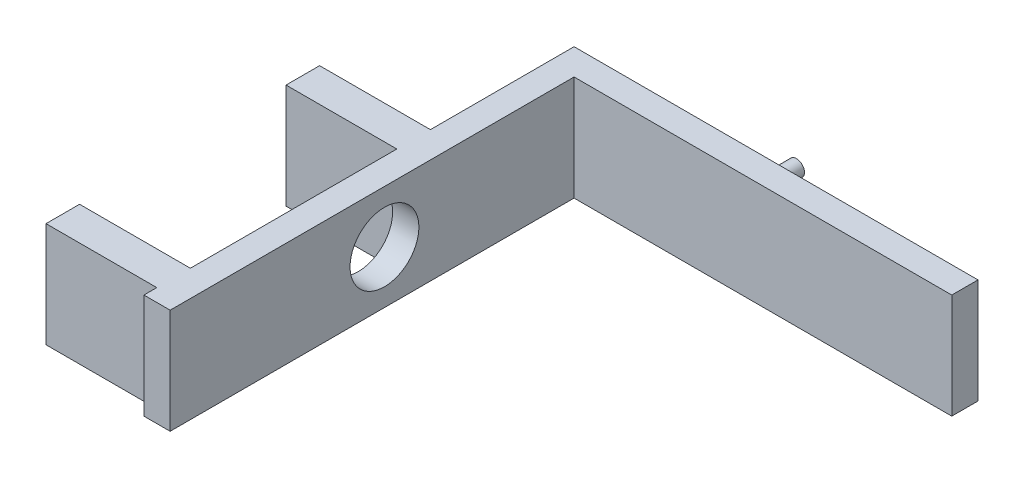
SolidWorks part; units mm, degrees
ref_plane "Front Plane" through (0, 0, 0) normal (0, 0, 1) x (1, 0, 0)
ref_plane "Top Plane" through (0, 0, 0) normal (0, 1, 0) x (1, 0, 0)
ref_plane "Right Plane" through (0, 0, 0) normal (1, 0, 0) x (0, 0, -1)
sketch "Sketch1" plane through (0, 0, 0) normal (0, 1, 0) x (1, 0, 0)
  line L1 (-2.7577, -19.8611) -> (1.211, -19.8611)
  line L2 (-2.7577, -19.8611) -> (-2.7577, 45.2264)
  line L3 (-2.7577, 45.2264) -> (6.2797, 45.2264)
  line L4 (1.211, -19.8611) -> (1.211, 41.2577)
  line L5 (-2.7577, -19.8611) -> (6.2797, 45.2264) construction
  line L6 (-2.7577, 45.2264) -> (1.211, -19.8611) construction
  line L7 (6.2797, 45.2264) -> (58.361, 45.2264)
  line L9 (1.211, 41.2577) -> (58.361, 41.2577)
  line L10 (58.361, 45.2264) -> (58.361, 41.2577)
  point P0 (0, 0)
  dimension "D1" = 3.9688
  dimension "D2" = 3.9688
  dimension "D3" = 57.15
  dimension "D4" = 61.1187
extrude "Boss-Extrude1" add sketch "Sketch1" along normal mid plane 15.875
sketch "Sketch3" plane through (-2.7577, 0, 0) normal (-1, 0, 0) x (0, 0, 1)
  circle A0 centre (-12.5666, 0) radius 5.207
  dimension "D1" = 10.414
extrude "Cut-Extrude1" cut sketch "Sketch3" against normal up to surface (3.9688 mm away) up to face at (1.211, 0, -10.6983)
sketch "Sketch4" plane through (0, 0, -45.2264) normal (0, 0, -1) x (-1, 0, 0)
  line L0 (-58.361, 7.9375) -> (-58.361, -7.9375) construction
  circle A0 centre (-22.0073, 0) radius 1.2065
  dimension "D1" = 2.413
  dimension "D2" = 36.3537
extrude "Boss-Extrude2" add sketch "Sketch4" along normal blind 8.89
sketch "Sketch5" plane through (-2.7577, 0, 0) normal (-1, 0, 0) x (0, 0, 1)
  line L0 (-45.2264, 7.9375) -> (19.8611, 7.9375) construction
  line L1 (-23.4886, -7.9375) -> (-18.4086, -7.9375)
  line L2 (-23.4886, -7.9375) -> (-23.4886, 7.9375)
  line L3 (-23.4886, 7.9375) -> (-18.4086, 7.9375)
  line L4 (-18.4086, -7.9375) -> (-18.4086, 7.9375)
  line L5 (-23.4886, -7.9375) -> (-18.4086, 7.9375) construction
  line L6 (-23.4886, 7.9375) -> (-18.4086, -7.9375) construction
  line L7 (-45.2264, -7.9375) -> (19.8611, -7.9375) construction
  line L9 (17.9134, 7.9375) -> (12.8334, 7.9375)
  line L10 (17.9134, 7.9375) -> (17.9134, -7.9375)
  line L11 (17.9134, -7.9375) -> (12.8334, -7.9375)
  line L12 (12.8334, 7.9375) -> (12.8334, -7.9375)
  circle A1 centre (-12.5666, 0) radius 5.207 construction
  point P0 (-20.9486, 0)
  dimension "D3" = 25.4
  dimension "D1" = 5.842
  dimension "D2" = 5.08
  dimension "D4" = 5.08
extrude "Boss-Extrude3" add sketch "Sketch5" along normal blind 16.764
sketch "Sketch6" plane through (-19.5217, 0, 0) normal (-1, 0, 0) x (0, 0, 1)
  circle A0 centre (14.8556, 0) radius 1.143
  circle A1 centre (-21.0346, 0) radius 1.143
  dimension "D1" = 2.286
  dimension "D2" = 2.286
extrude "Cut-Extrude2" cut sketch "Sketch6" against normal blind 12.7
